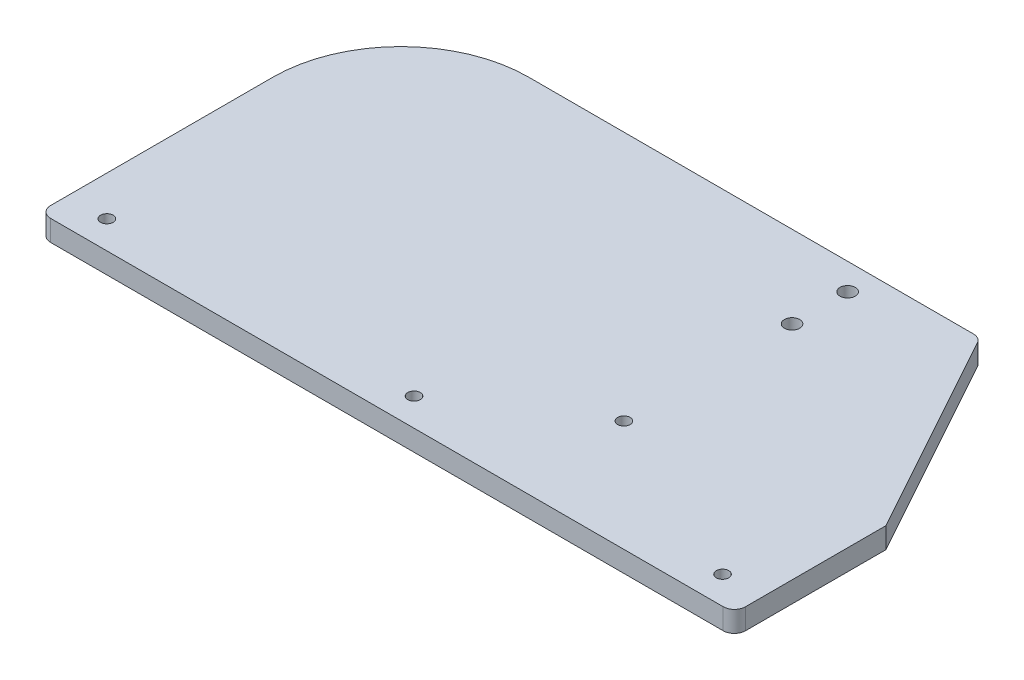
SolidWorks part; units mm, degrees
ref_plane "Front Plane" through (0, 0, 0) normal (0, 0, 1) x (1, 0, 0)
ref_plane "Top Plane" through (0, 0, 0) normal (0, 1, 0) x (1, 0, 0)
ref_plane "Right Plane" through (0, 0, 0) normal (1, 0, 0) x (0, 0, -1)
sketch "Sketch1" plane through (0, 0, 0) normal (0, 1, 0) x (1, 0, 0)
  line L0 (-170.25, 0) -> (79.75, 0) construction
  line L1 (0, -10) -> (0, 120) construction
  line L2 (-166.25, -10) -> (75.75, -10)
  line L3 (79.75, -6) -> (79.75, 44.5)
  line L4 (79.75, 44.5) -> (39.2526, 117.9317)
  line L5 (35.75, 120) -> (-124.25, 120)
  line L6 (-170.25, 74) -> (-170.25, -6)
  arc A0 (75.75, -10) -> (79.75, -6) centre (75.75, -6) ccw
  arc A1 (39.2526, 117.9317) -> (35.75, 120) centre (35.75, 116) ccw
  arc A2 (-124.25, 120) -> (-170.25, 74) centre (-124.25, 74) ccw
  arc A3 (-170.25, -6) -> (-166.25, -10) centre (-166.25, -6) ccw
  circle A4 centre (0, 30) radius 2 construction
  circle A5 centre (65.5, 0) radius 2.25
  circle A6 centre (-45.5, 0) radius 2.25
  circle A7 centre (-156, 0) radius 2.25
  circle A8 centre (0, 90.5) radius 2.75
  circle A9 centre (0, 110.5) radius 2.5 construction
  circle A10 centre (0, 110.5) radius 2.75
  circle A11 centre (0, 30) radius 2.25
  dimension "D3" = 5
  dimension "D4" = 4
  dimension "D10" = 4
  dimension "D6" = 130
  dimension "D13" = 160
  dimension "D14" = 54.5
  dimension "D15" = 80
  dimension "D5" = 10
  dimension "D7" = 30
  dimension "D8" = 60.5
  dimension "D9" = 20
  dimension "D11" = 65.5
  dimension "D12" = 45.5
  dimension "D16" = 110.5
  dimension "D17" = 250
  dimension "D18" = 14.25
  dimension "D19" = 14.25
  dimension "D20" = 9.5
  dimension "D1" = 0.25
  dimension "D2" = 0.25
extrude "Boss-Extrude1" add sketch "Sketch1" along normal blind 7.5
equation "\"Tolerance\"=0.25"
equation "\"D1@Sketch1\"=\"Tolerance\""
equation "\"D2@Sketch1\"=\"Tolerance\""
